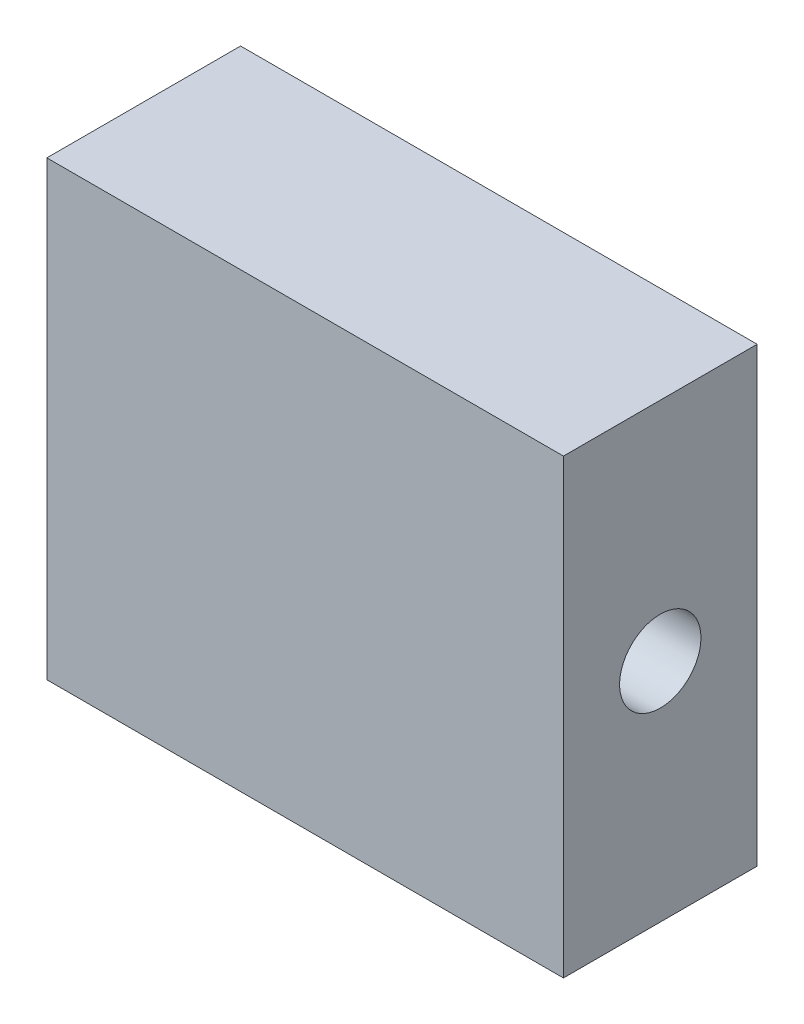
SolidWorks part; units mm, degrees
ref_plane "Front Plane" through (0, 0, 0) normal (0, 0, 1) x (1, 0, 0)
ref_plane "Top Plane" through (0, 0, 0) normal (0, 1, 0) x (1, 0, 0)
ref_plane "Right Plane" through (0, 0, 0) normal (1, 0, 0) x (0, 0, -1)
sketch "Sketch1" plane through (0, 0, 0) normal (1, 0, 0) x (0, 0, -1)
  line L1 (-7.5, 17.5) -> (7.5, 17.5)
  line L2 (-7.5, 17.5) -> (-7.5, -17.5)
  line L3 (-7.5, -17.5) -> (7.5, -17.5)
  line L4 (7.5, 17.5) -> (7.5, -17.5)
  line L5 (-7.5, 17.5) -> (7.5, -17.5) construction
  line L6 (-7.5, -17.5) -> (7.5, 17.5) construction
  circle A0 centre (0, 0) radius 3.15
  point P0 (0, 0)
  dimension "D3" = 6.3
  dimension "D1" = 15
  dimension "D2" = 35
extrude "Boss-Extrude1" add sketch "Sketch1" along normal blind 40
